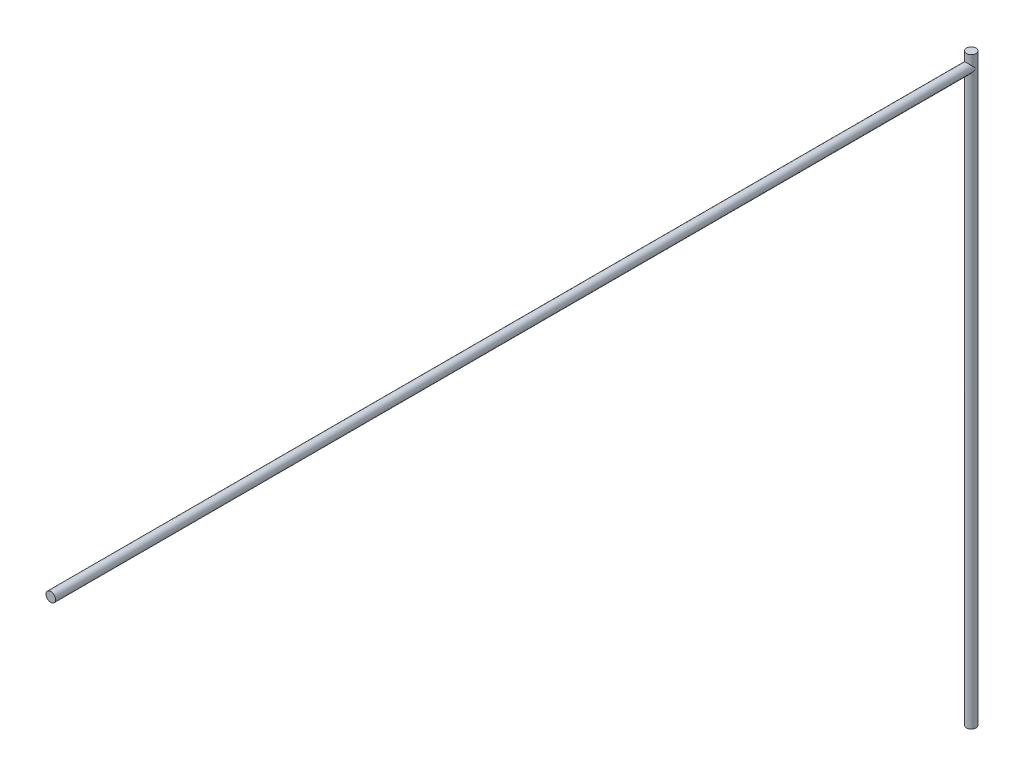
SolidWorks part; units mm, degrees
ref_plane "前视基准面" through (0, 0, 0) normal (0, 0, 1) x (1, 0, 0)
ref_plane "上视基准面" through (0, 0, 0) normal (0, 1, 0) x (1, 0, 0)
ref_plane "右视基准面" through (0, 0, 0) normal (1, 0, 0) x (0, 0, -1)
sketch "草图1" plane through (0, 0, 0) normal (0, 0, 1) x (1, 0, 0)
  circle A0 centre (0, 0) radius 0.75
  dimension "D1" = 1.5
extrude "凸台-拉伸1" add sketch "草图1" along normal blind 145
sketch "草图2" plane through (0, 0, 0) normal (0, 1, 0) x (1, 0, 0)
  circle A0 centre (0, 0) radius 0.75
  dimension "D1" = 1.5
extrude "凸台-拉伸2" add sketch "草图2" against normal blind 90 and the other way blind 2
